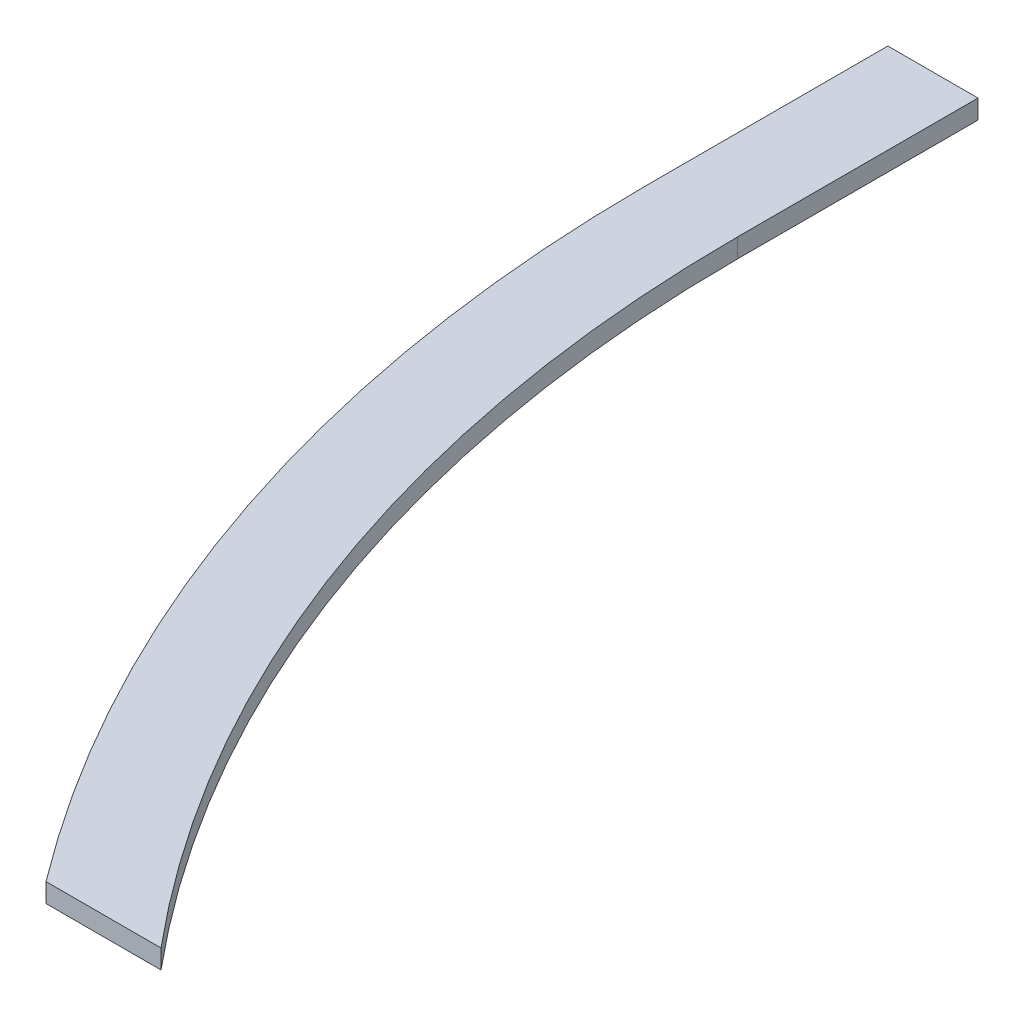
SolidWorks part; units mm, degrees
material "Pine"
ref_plane "Front Plane" through (0, 0, 0) normal (0, 0, 1) x (1, 0, 0)
ref_plane "Top Plane" through (0, 0, 0) normal (0, 1, 0) x (1, 0, 0)
ref_plane "Right Plane" through (0, 0, 0) normal (1, 0, 0) x (0, 0, -1)
sketch "Sketch2" plane through (0, 0, 0) normal (0, 1, 0) x (1, 0, 0)
  line L0 (0, 0) -> (-500, 0)
  line L1 (0, 0) -> (0, -500)
  circle A0 centre (0, 0) radius 500
  circle A1 centre (0, 0) radius 470
  dimension "D1" = 1000
  dimension "D2" = 30
extrude "Boss-Extrude1" add sketch "Sketch2" along normal blind 6.35 contours A1 L0 A0 L1
sketch "Sketch3" plane through (0, 0, 0) normal (0, 0, -1) x (-1, 0, 0)
  line L8 (470, 0) -> (500, 0)
  line L9 (500, 0) -> (500, 6.35)
  line L10 (500, 6.35) -> (470, 6.35)
  line L11 (470, 6.35) -> (470, 0)
  line L12 (470, 0) -> (500, 0)
  line L13 (500, 0) -> (500, 6.35)
  line L14 (500, 6.35) -> (470, 6.35)
  line L15 (470, 6.35) -> (470, 0)
  dimension "D1" = 0
extrude "Boss-Extrude2" add sketch "Sketch3" along normal blind 80
sketch "Sketch4" plane through (0, 6.35, 0) normal (0, 1, 0) x (1, 0, 0)
  line L1 (-500, 80) -> (0, 80) construction
  line L2 (-500, 80) -> (-500, -500) construction
  line L3 (-500, -500) -> (0, -500) construction
  line L4 (0, 80) -> (0, -500) construction
  line L5 (-500, 80) -> (-195.2, 80) construction
  line L6 (-500, 80) -> (-500, -326.4) construction
  line L7 (-500, -326.4) -> (-195.2, -326.4) construction
  line L8 (-195.2, 80) -> (-195.2, -326.4) construction
  line L9 (0, -500) -> (-406.4, -500) construction
  line L10 (0, -500) -> (0, -195.2) construction
  line L11 (0, -195.2) -> (-406.4, -195.2) construction
  line L12 (-406.4, -500) -> (-406.4, -195.2) construction
  dimension "D1" = 304.8
  dimension "D2" = 406.4
  dimension "D3" = 304.8
  dimension "D4" = 406.4
ref_plane "Plane1" through (0, 0, 301) normal (0, 0, -1) x (-1, 0, 0)
split "Split1" trim tools "Plane1" bodies to split 102 resulting bodies 104
